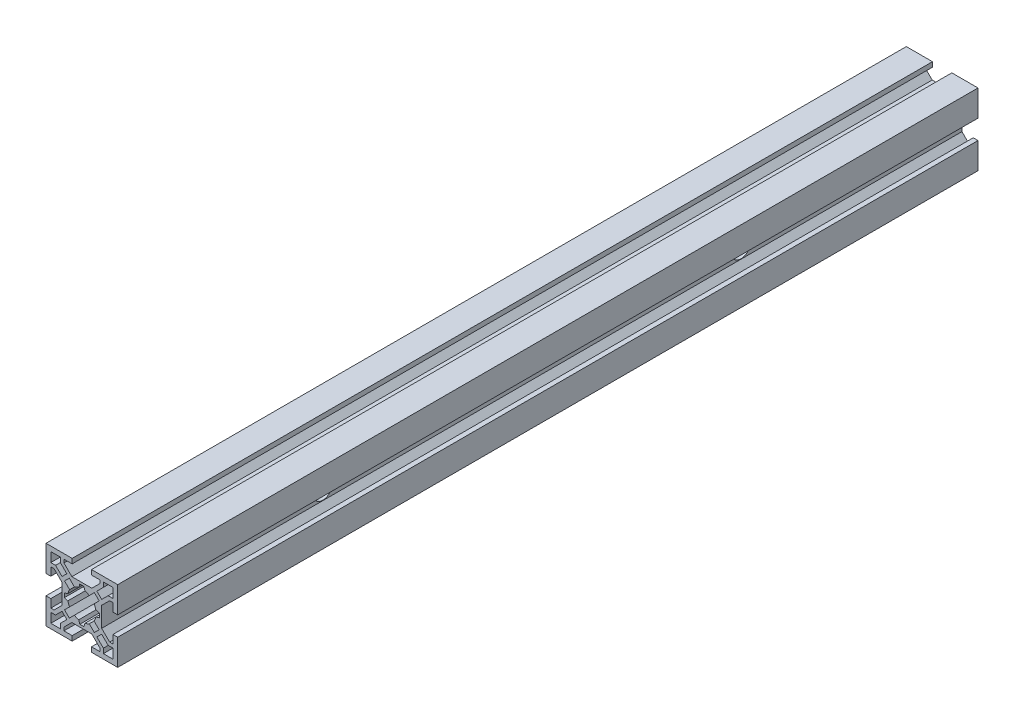
SolidWorks part; units mm, degrees
material "Liga 1060"
ref_plane "Plano frontal" through (0, 0, 0) normal (0, 0, 1) x (1, 0, 0)
ref_plane "Plano superior" through (0, 0, 0) normal (0, 1, 0) x (1, 0, 0)
ref_plane "Plano direito" through (0, 0, 0) normal (1, 0, 0) x (0, 0, -1)
ref_plane "Plano1" through (0, 0, 100) normal (0, 0, 1) x (1, 0, 0)
sketch "Esboço1" plane through (0, 0, 0) normal (0, 0, 1) x (1, 0, 0)
  line L0 (0, 0) -> (-15, -15) construction
  line L1 (-13, -4.05) -> (-15, -4.05)
  line L2 (-11.6273, -7.5) -> (-8.3, -4.1727)
  line L3 (-15, -15) -> (-4.05, -15)
  line L4 (-11.6273, -7.5) -> (-13, -7.5)
  line L5 (-7.5, -13) -> (-4.05, -13)
  line L6 (-7.2393, -5.2334) -> (-5.1254, -3.1194)
  line L7 (-8.3, -4.1727) -> (-8.3, 4.1727)
  line L8 (-11.006, -9) -> (-13, -9)
  line L9 (-13, -13) -> (-9, -13)
  line L10 (-13, -13) -> (-13, -9)
  line L11 (-13, -7.5) -> (-13, -4.05)
  line L12 (-15, -15) -> (-15, -4.05)
  line L13 (0, 0) -> (0, -8.3) construction
  line L14 (0, 0) -> (-8.3, 0) construction
  line L15 (7.2393, -5.2334) -> (5.2334, -7.2393)
  line L16 (4.05, -13) -> (4.05, -15)
  line L17 (-9, -11.006) -> (-9, -13)
  line L18 (0, 0) -> (0, 7.3) construction
  line L19 (7.5, -11.6273) -> (4.1727, -8.3)
  line L20 (7.5, -11.6273) -> (7.5, -13)
  line L21 (5.2334, -7.2393) -> (3.1194, -5.1254)
  line L22 (9, -11.006) -> (9, -13)
  line L23 (15, -15) -> (15, -4.05)
  line L24 (13, -7.5) -> (13, -4.05)
  line L25 (13, -13) -> (13, -9)
  line L26 (13, -13) -> (9, -13)
  line L27 (11.006, -9) -> (13, -9)
  line L28 (-4.1727, -8.3) -> (4.1727, -8.3)
  line L29 (8.3, -4.1727) -> (8.3, 4.1727)
  line L30 (7.2393, -5.2334) -> (5.1254, -3.1194)
  line L31 (7.5, -13) -> (4.05, -13)
  line L32 (11.6273, -7.5) -> (13, -7.5)
  line L33 (15, -15) -> (4.05, -15)
  line L34 (11.6273, -7.5) -> (8.3, -4.1727)
  line L35 (13, -4.05) -> (15, -4.05)
  line L36 (-7.2393, 5.2334) -> (-5.2334, 7.2393)
  line L37 (-4.05, 13) -> (-4.05, 15)
  line L38 (-7.5, 11.6273) -> (-4.1727, 8.3)
  line L39 (-7.5, 11.6273) -> (-7.5, 13)
  line L40 (-5.2334, 7.2393) -> (-3.1194, 5.1254)
  line L41 (13, 4.05) -> (15, 4.05)
  line L42 (11.6273, 7.5) -> (8.3, 4.1727)
  line L43 (15, 15) -> (4.05, 15)
  line L44 (11.6273, 7.5) -> (13, 7.5)
  line L45 (7.5, 13) -> (4.05, 13)
  line L46 (7.2393, 5.2334) -> (5.1254, 3.1194)
  line L47 (-5.2334, -7.2393) -> (-3.1194, -5.1254)
  line L48 (-4.1727, 8.3) -> (4.1727, 8.3)
  line L49 (11.006, 9) -> (13, 9)
  line L50 (13, 13) -> (9, 13)
  line L51 (13, 13) -> (13, 9)
  line L52 (13, 7.5) -> (13, 4.05)
  line L53 (15, 15) -> (15, 4.05)
  line L54 (9, 11.006) -> (9, 13)
  line L55 (5.2334, 7.2393) -> (3.1194, 5.1254)
  line L56 (-7.5, -11.6273) -> (-7.5, -13)
  line L57 (7.5, 11.6273) -> (7.5, 13)
  line L58 (7.5, 11.6273) -> (4.1727, 8.3)
  line L59 (-9, 11.006) -> (-9, 13)
  line L60 (-7.5, -11.6273) -> (-4.1727, -8.3)
  line L61 (4.05, 13) -> (4.05, 15)
  line L62 (7.2393, 5.2334) -> (5.2334, 7.2393)
  line L63 (-15, 15) -> (-15, 4.05)
  line L64 (-13, 7.5) -> (-13, 4.05)
  line L65 (-13, 13) -> (-13, 9)
  line L66 (-13, 13) -> (-9, 13)
  line L67 (-11.006, 9) -> (-13, 9)
  line L68 (-7.2393, 5.2334) -> (-5.1254, 3.1194)
  line L69 (-4.05, -13) -> (-4.05, -15)
  line L70 (-7.5, 13) -> (-4.05, 13)
  line L71 (-11.6273, 7.5) -> (-13, 7.5)
  line L72 (-15, 15) -> (-4.05, 15)
  line L73 (-11.6273, 7.5) -> (-8.3, 4.1727)
  line L74 (-13, 4.05) -> (-15, 4.05)
  line L75 (-6.294, -8.3) -> (-8.3, -6.294)
  line L76 (-6.294, -8.3) -> (-9, -11.006)
  line L77 (-8.3, -6.294) -> (-11.006, -9)
  line L78 (-8.3, 6.294) -> (-11.006, 9)
  line L79 (-6.294, 8.3) -> (-8.3, 6.294)
  line L80 (-6.294, 8.3) -> (-9, 11.006)
  line L81 (6.294, 8.3) -> (9, 11.006)
  line L82 (6.294, 8.3) -> (8.3, 6.294)
  line L83 (8.3, 6.294) -> (11.006, 9)
  line L84 (6.294, -8.3) -> (9, -11.006)
  line L85 (6.294, -8.3) -> (8.3, -6.294)
  line L86 (8.3, -6.294) -> (11.006, -9)
  line L87 (5.8582, -1.2966) -> (7.3, -0.8598)
  line L88 (7.3, -0.8598) -> (7.3, 0.8598)
  line L89 (5.8582, 1.2966) -> (7.3, 0.8598)
  line L90 (-1.2966, -5.8582) -> (-0.8598, -7.3)
  line L91 (-0.8598, -7.3) -> (0.8598, -7.3)
  line L92 (1.2966, -5.8582) -> (0.8598, -7.3)
  line L93 (1.2966, 5.8582) -> (0.8598, 7.3)
  line L94 (0.8598, 7.3) -> (-0.8598, 7.3)
  line L95 (-1.2966, 5.8582) -> (-0.8598, 7.3)
  line L96 (-5.8582, 1.2966) -> (-7.3, 0.8598)
  line L97 (-7.3, 0.8598) -> (-7.3, -0.8598)
  line L98 (-5.8582, -1.2966) -> (-7.3, -0.8598)
  line L99 (-7.2393, -5.2334) -> (-5.2334, -7.2393)
  arc A0 (-5.1254, -3.1194) -> (-5.8582, -1.2966) centre (0, 0) cw
  arc A1 (5.1254, -3.1194) -> (5.8582, -1.2966) centre (0, 0) ccw
  arc A2 (-3.1194, 5.1254) -> (-1.2966, 5.8582) centre (0, 0) cw
  arc A3 (-3.1194, -5.1254) -> (-1.2966, -5.8582) centre (0, 0) ccw
  arc A4 (1.2966, -5.8582) -> (3.1194, -5.1254) centre (0, 0) ccw
  arc A5 (5.8582, 1.2966) -> (5.1254, 3.1194) centre (0, 0) ccw
  arc A6 (1.2966, 5.8582) -> (3.1194, 5.1254) centre (0, 0) cw
  arc A7 (-5.8582, 1.2966) -> (-5.1254, 3.1194) centre (0, 0) cw
  point P4 (6.2364, 6.2364)
  point P6 (-6.2364, -6.2364)
  point P17 (6.2364, -6.2364)
  point P41 (-6.2364, 6.2364)
  point P60 (8.3, 0)
  point P85 (-7.297, -7.297)
  point P109 (0, 7.3)
  point P111 (7.3, 0)
  point P112 (0, 0)
  point P115 (0, -7.3)
  point P118 (-7.3, 0)
  point P119 (0, 0)
  dimension "D2" = 6
  dimension "D1" = 2
  dimension "D3" = 5.8368
  dimension "D4" = 1.5
  dimension "D5" = 1.5
  dimension "D6" = 1
  dimension "D7" = 1.7196
  dimension "D8" = 2.5933
  dimension "D9" = 30
  dimension "D10" = 8.1
  dimension "D11" = 15
  dimension "D12" = 1.5
extrude "Ressalto-extrusão1" add sketch "Esboço1" against normal mid plane 360
sketch "Esboço2" plane through (0, 0, 0) normal (1, 0, 0) x (0, 0, -1)
  line L0 (0, 0) -> (0, 42.8528) construction
  line L1 (0, 0) -> (87.5, 0) construction
  line L2 (-87.5, 0) -> (-87.5, -15) construction
  line L3 (180, -15) -> (-180, -15) construction
  circle A0 centre (87.5, 0) radius 4
  circle A1 centre (-87.5, 0) radius 4
  circle A2 centre (-87.5, -15) radius 4 construction
  circle A3 centre (87.5, -15) radius 4 construction
  circle A4 centre (87.5, 15) radius 4 construction
  circle A5 centre (-87.5, 15) radius 4 construction
  dimension "D1" = 8
  dimension "D2" = 175
extrude "Corte-extrusão1" cut sketch "Esboço2" against normal through all and the other way through all
